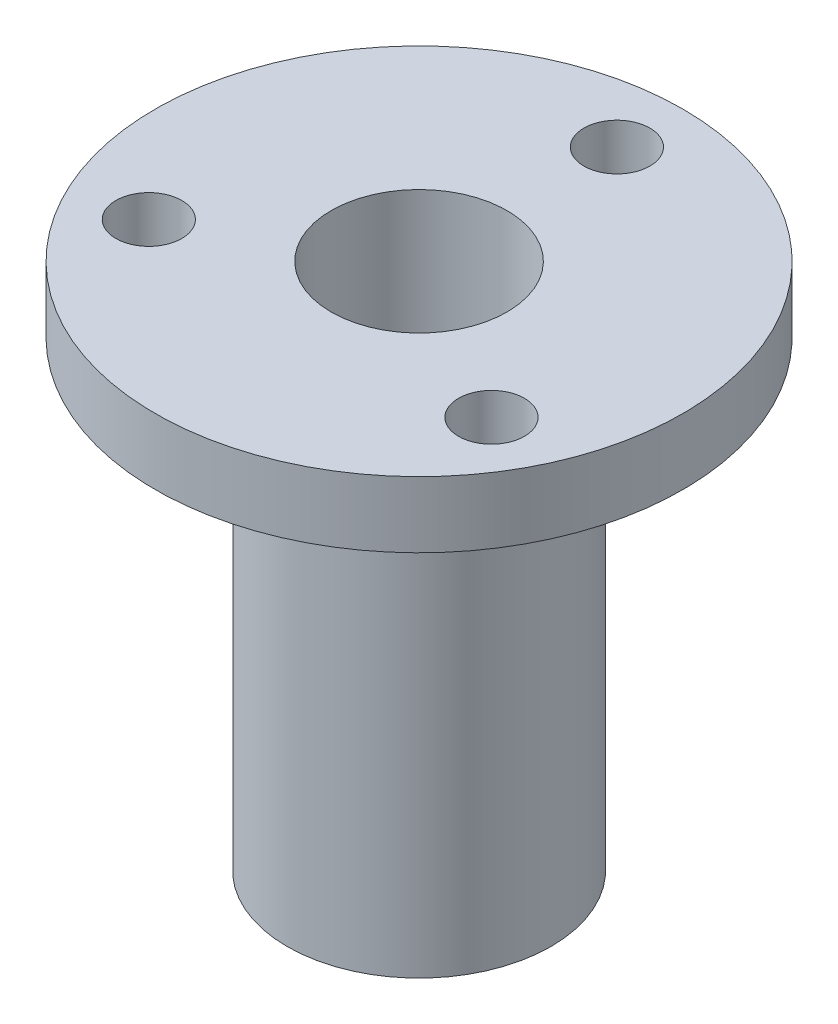
SolidWorks part; units mm, degrees
ref_plane "Front Plane" through (0, 0, 0) normal (0, 0, 1) x (1, 0, 0)
ref_plane "Top Plane" through (0, 0, 0) normal (0, 1, 0) x (1, 0, 0)
ref_plane "Right Plane" through (0, 0, 0) normal (1, 0, 0) x (0, 0, -1)
sketch "Sketch1" plane through (0, 0, 0) normal (0, 1, 0) x (1, 0, 0)
  circle A0 centre (0, 0) radius 19.05
  dimension "D1" = 38.1
extrude "Boss-Extrude1" add sketch "Sketch1" along normal blind 38.1
sketch "Sketch2" plane through (0, 0, 0) normal (0, -1, 0) x (1, 0, 0)
  circle A0 centre (0, 0) radius 19.05
  circle A1 centre (0, 0) radius 9.525
  dimension "D1" = 19.05
  dimension "D2" = 38.1
extrude "Cut-Extrude1" cut sketch "Sketch2" against normal blind 33.3375
sketch "Sketch3" plane through (0, 38.1, 0) normal (0, 1, 0) x (1, 0, 0)
  line L0 (0, 0) -> (-16.4978, -9.525) construction
  line L1 (0, 0) -> (16.4978, -9.525) construction
  line L2 (0, 0) -> (0, 19.05) construction
  circle A0 centre (0, 0) radius 6.35
  circle A1 centre (0, 0) radius 19.05 construction
  circle A2 centre (0, 14.2875) radius 2.3812
  circle A3 centre (12.3733, -7.1437) radius 2.3813
  circle A4 centre (-12.3733, -7.1438) radius 2.3813
  dimension "D1" = 12.7
  dimension "D4" = 4.7625
  dimension "D5" = 4.7625
  dimension "D6" = 4.7625
  dimension "D2" = 120
  dimension "D3" = 120
  dimension "D7" = 4.7625
  dimension "D8" = 4.7625
  dimension "D9" = 4.7625
extrude "Cut-Extrude2" cut sketch "Sketch3" against normal blind 38.1
